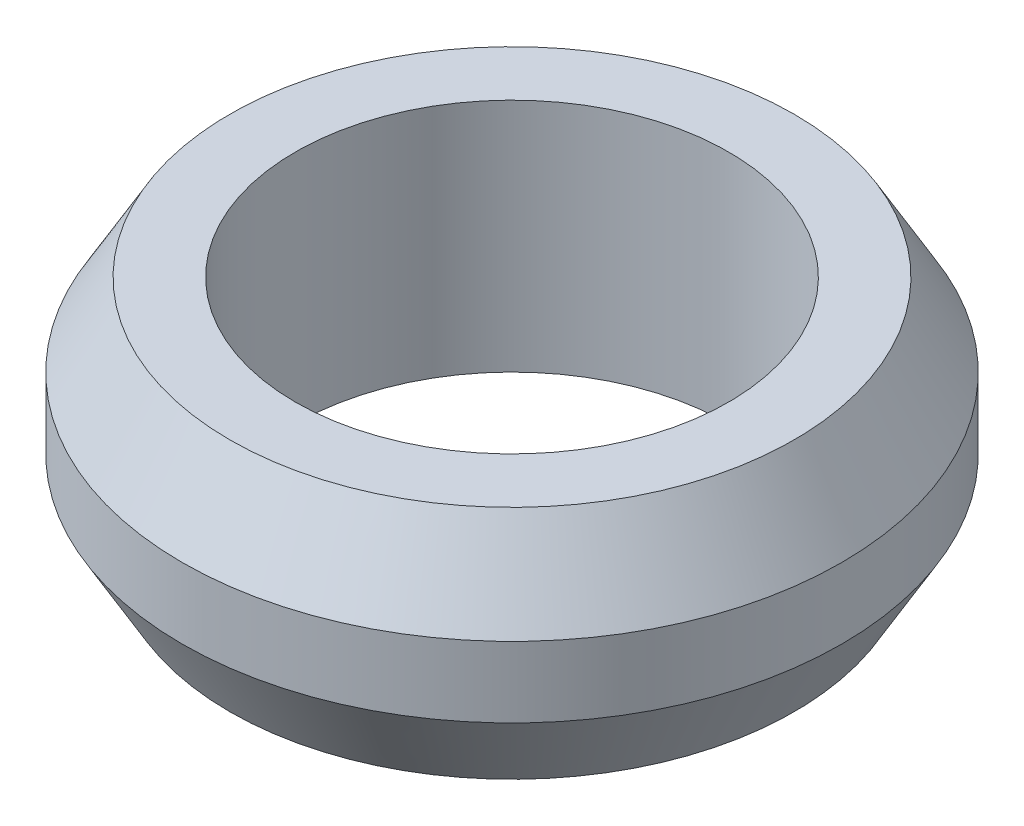
SolidWorks part; units mm, degrees
ref_plane "前视基准面" through (0, 0, 0) normal (0, 0, 1) x (1, 0, 0)
ref_plane "上视基准面" through (0, 0, 0) normal (0, 1, 0) x (1, 0, 0)
ref_plane "右视基准面" through (0, 0, 0) normal (1, 0, 0) x (0, 0, -1)
sketch "草图2" plane through (0, 0, 0) normal (0, 0, 1) x (1, 0, 0)
  line L0 (-5.9896, 0) -> (-7, 1.75)
  line L1 (-7, 1.75) -> (-7, 3.25)
  line L2 (-7, 3.25) -> (-5.9896, 5)
  line L3 (-5.9896, 5) -> (-4.6, 5)
  line L4 (-4.6, 5) -> (-4.6, 0)
  line L5 (-4.6, 0) -> (-5.9896, 0)
  line L6 (0, 6.3686) -> (0, -3.0642) construction
  line L7 (-4.6, 2.5) -> (-11.405, 2.5) construction
  dimension "D1" = 60
  dimension "D2" = 5
  dimension "D3" = 1.5
  dimension "D4" = 4.6
  dimension "D5" = 7
  dimension "D6" = 7
  dimension "D7" = 7
revolve "旋转1" add sketch "草图2" angle 360 about L6
